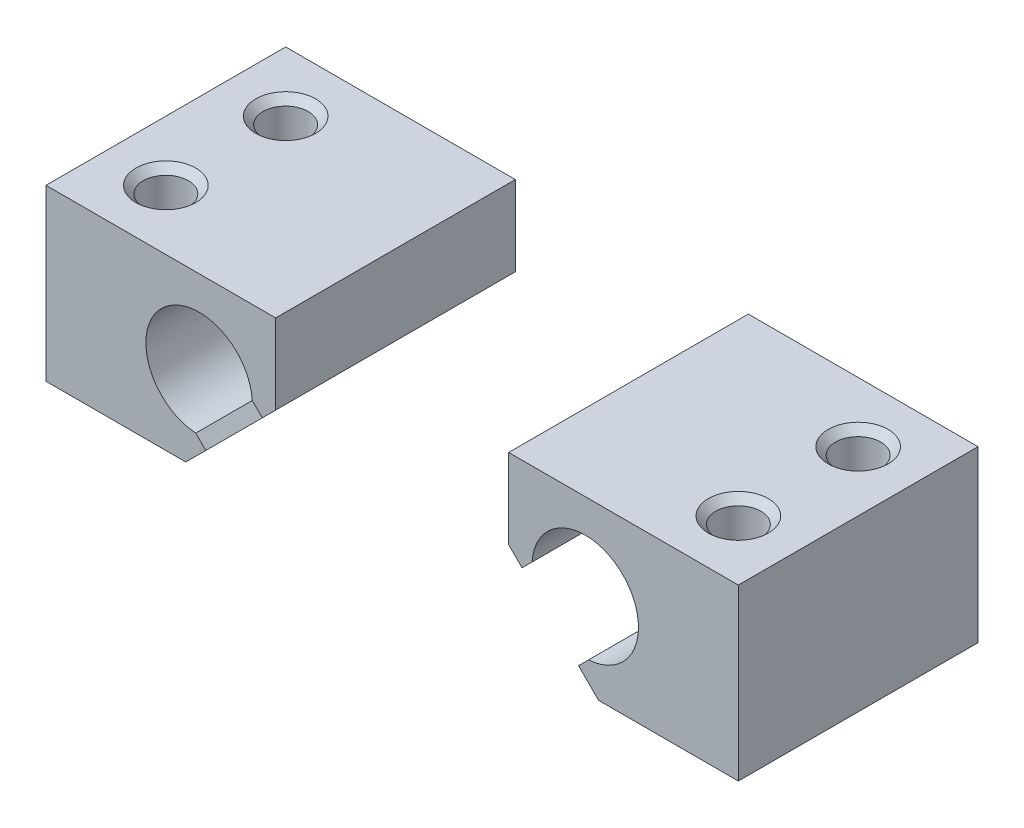
SolidWorks part; units mm, degrees
ref_plane "Front Plane" through (0, 0, 0) normal (0, 0, 1) x (1, 0, 0)
ref_plane "Top Plane" through (0, 0, 0) normal (0, 1, 0) x (1, 0, 0)
ref_plane "Right Plane" through (0, 0, 0) normal (1, 0, 0) x (0, 0, -1)
sketch "Sketch1" plane through (0, 0, 0) normal (0, 0, 1) x (1, 0, 0)
  line L0 (19.5074, -14.0074) -> (17.5, -12)
  line L1 (17.5, -12) -> (17.5, 0)
  line L2 (17.5, 0) -> (52, 0)
  line L3 (52, 0) -> (52, -25.5)
  line L4 (52, -25.5) -> (31, -25.5)
  line L5 (31, -25.5) -> (27.9926, -22.4926)
  line L6 (0, -6.8948) -> (0, -29.6073) construction
  line L7 (19.5074, -14.0074) -> (21.0157, -12.499)
  line L8 (27.9926, -22.4926) -> (29.501, -20.9843)
  arc A0 (29.501, -20.9843) -> (21.0157, -12.499) centre (29, -13) ccw
  circle A1 centre (29, -13) radius 6 construction
  point P2 (43, 0)
  dimension "D2" = 8
  dimension "D3" = 13
  dimension "D4" = 23
  dimension "D6" = 7.4246
  dimension "D9" = 12
  dimension "D10" = 58
  dimension "D1" = 45
  dimension "D5" = 34.5
  dimension "D7" = 25.5
  dimension "D8" = 21
  dimension "D11" = 86
  dimension "D12" = 9
extrude "Boss-Extrude1" add sketch "Sketch1" along normal mid plane 36
hole_wizard "M8x1.25 Tapped Hole1" positions "Sketch3" profile "Sketch2" tap size "M8x1.25" standard "Ansi Metric" end condition through all
sketch "Sketch3" plane through (0, 0, 0) normal (0, 1, 0) x (-1, 0, 0)
  point P0 (-43, -9)
  point P1 (-43, 9)
  dimension "D1" = 9
  dimension "D2" = 9
sketch "Sketch2" plane through (43, 0, -9) normal (1, 0, 0) x (0, 0, 1)
  line L0 (0, 0) -> (0, 25.5)
  line L1 (0, 25.5) -> (3.4, 25.5)
  line L2 (3.4, 25.5) -> (3.4, 1.1)
  line L3 (3.4, 1.1) -> (4.5, 0)
  line L5 (4.5, 0) -> (0, 0)
  line L6 (-3.4, 1.1) -> (-4.5, 0) construction
  line L11 (0, -6.35) -> (0, 107.95) construction
  dimension "Thread Major Dia." = 6.8
  dimension "Thru Tap Drill Depth" = 25.5
  dimension "Near C'Sink Dia." = 9
  dimension "Near C'Sink Angle" = 90
mirror "Mirror2" about plane through (0, 0, 0) normal (1, 0, 0) of bodies 104
